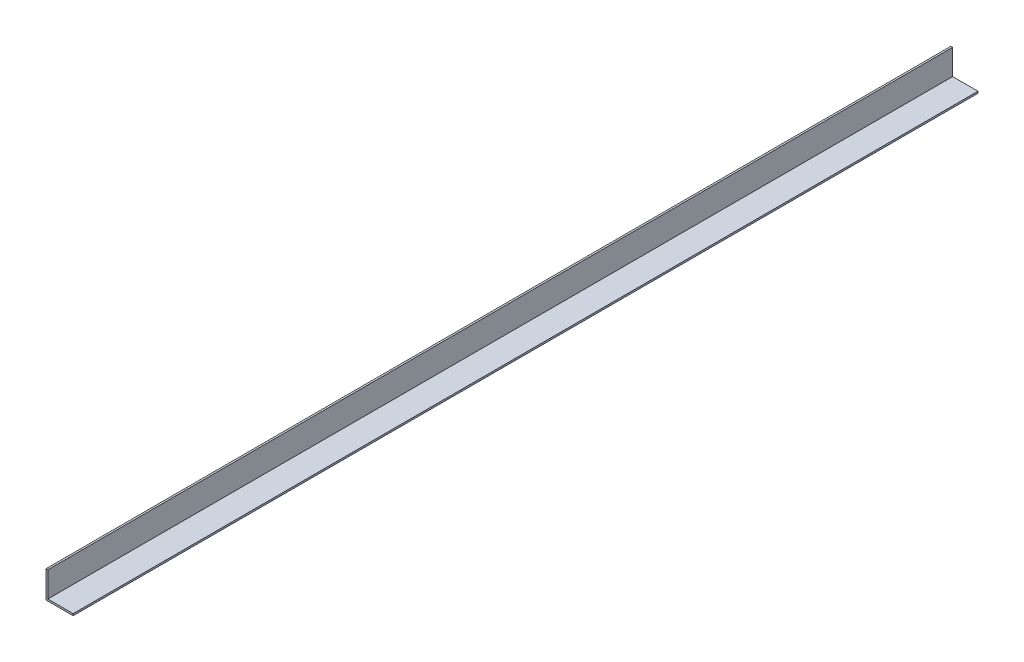
SolidWorks part; units mm, degrees
ref_plane "Front Plane" through (0, 0, 0) normal (0, 0, 1) x (1, 0, 0)
ref_plane "Top Plane" through (0, 0, 0) normal (0, 1, 0) x (1, 0, 0)
ref_plane "Right Plane" through (0, 0, 0) normal (1, 0, 0) x (0, 0, -1)
sketch "Sketch1" plane through (0, 0, 0) normal (0, 0, 1) x (1, 0, 0)
  line L1 (0, 0) -> (-30, 0)
  line L3 (-28, 30) -> (-30, 30)
  line L4 (-30, 0) -> (-30, 30)
  line L5 (-28, 2) -> (-28, 28)
  line L6 (0, 2) -> (-28, 2)
  line L8 (-28, 28) -> (-28, 30)
  line L9 (0, 2) -> (0, 0)
  line L10 (2, 30) -> (-30, 30) construction
  line L11 (0, 28) -> (-28, 28) construction
  line L12 (0, 2) -> (0, 28) construction
  line L13 (2, 0) -> (2, 30) construction
  line L14 (2, 0) -> (-30, 0) construction
  dimension "D1" = 30
  dimension "D2" = 30
  dimension "D3" = 2
extrude "Boss-Extrude1" add sketch "Sketch1" along normal blind 1000
